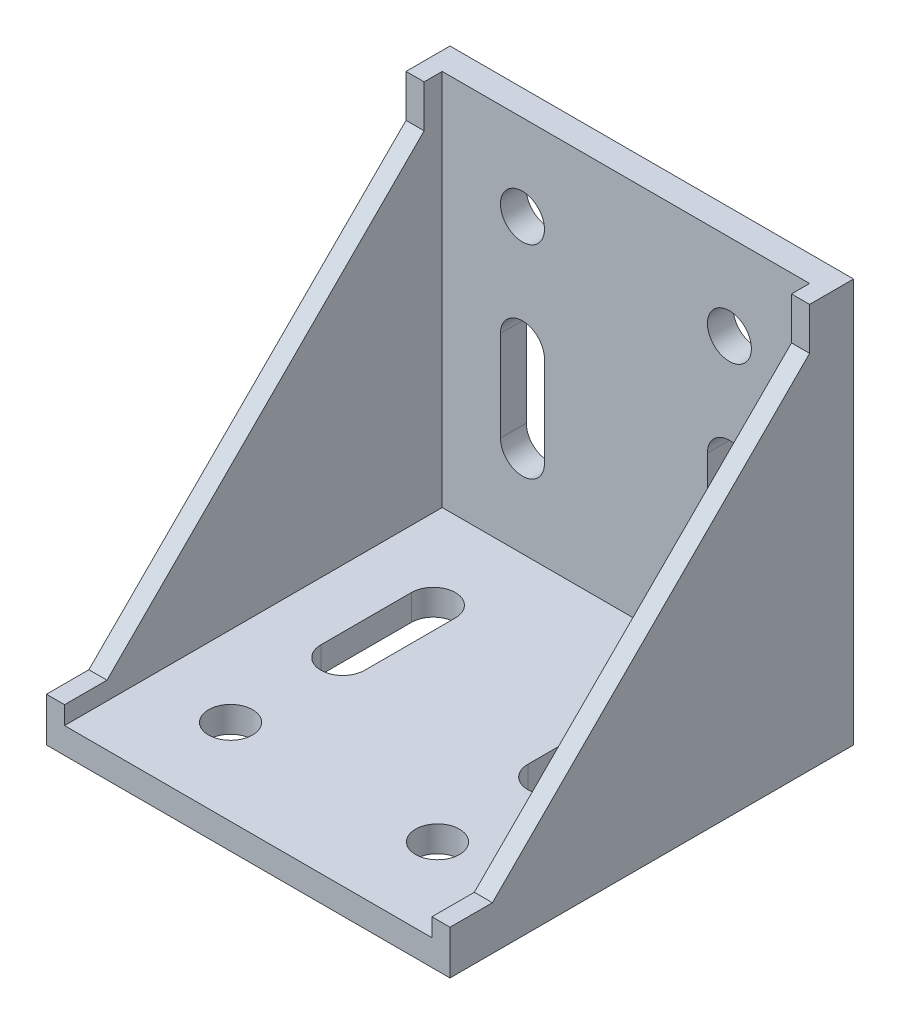
SolidWorks part; units mm, degrees
ref_plane "前视基准面" through (0, 0, 0) normal (0, 0, 1) x (1, 0, 0)
ref_plane "上视基准面" through (0, 0, 0) normal (0, 1, 0) x (1, 0, 0)
ref_plane "右视基准面" through (0, 0, 0) normal (1, 0, 0) x (0, 0, -1)
sketch "草图3" plane through (0, 0, 0) normal (0, 0, 1) x (1, 0, 0)
  line L1 (-39, 78) -> (39, 78)
  line L2 (-39, 78) -> (-39, 0)
  line L3 (-39, 0) -> (39, 0)
  line L4 (39, 78) -> (39, 0)
  line L7 (0, 111.3933) -> (0, -42.6526) construction
  line L11 (-39, 39) -> (39, 39) construction
  point P4 (0, 0)
  circle B0 centre (-20, 61.45) radius 4.25
  circle B1 centre (20, 61.45) radius 4.25
  line B2 (-15.75, 39.75) -> (-15.75, 22.25)
  arc B3 (-24.25, 22.25) -> (-15.75, 22.25) centre (-20, 22.25) ccw
  line B4 (-24.25, 39.75) -> (-24.25, 22.25)
  arc B5 (-15.75, 39.75) -> (-24.25, 39.75) centre (-20, 39.75) ccw
  line B6 (15.75, 39.75) -> (15.75, 22.25)
  arc B7 (24.25, 22.25) -> (15.75, 22.25) centre (20, 22.25) cw
  line B8 (24.25, 39.75) -> (24.25, 22.25)
  arc B9 (15.75, 39.75) -> (24.25, 39.75) centre (20, 39.75) cw
  dimension "D1" = 78
  dimension "D2" = 78
  dimension "D7" = 16.55
sketch_block_instance "块2-1"
sketch_block "块2"
sketch_block_instance "块1-1"
sketch_block "块1" parameters "D3"=8.5, "D1"=26, "D2"=8.5, "D4"=21.7
extrude "凸台-拉伸1" add sketch "草图3" along normal blind 5
sketch "草图4" plane through (-39, 0, 0) normal (-1, 0, 0) x (0, 0, 1)
  line L0 (5, 78) -> (8.5, 78)
  line L1 (8.5, 78) -> (8.5, 69.8)
  line L2 (8.5, 69.8) -> (69.8, 8.5)
  line L3 (69.8, 8.5) -> (78, 8.5)
  line L4 (78, 8.5) -> (78, 0)
  line L5 (78, 0) -> (5, 0)
  line L6 (5, 0) -> (5, 78)
  line L7 (0, 78) -> (0, 0) construction
  dimension "D1" = 8.5
  dimension "D2" = 8.5
  dimension "D3" = 78
  dimension "D4" = 8.2
extrude "凸台-拉伸2" add sketch "草图4" against normal blind 3.5
mirror "镜向1" about plane through (0, 0, 0) normal (1, 0, 0) of "凸台-拉伸2"
sketch "草图5" plane through (0, 0, 0) normal (0, -1, 0) x (1, 0, 0)
  line L0 (0, 98.3646) -> (0, -20.4361) construction
  line L1 (-39, 0) -> (39, 0)
  line L2 (-39, 0) -> (-39, 78)
  line L3 (-39, 78) -> (39, 78)
  line L4 (39, 0) -> (39, 78)
  line L5 (-39, 39) -> (39, 39) construction
  circle B0 centre (-20, 61.4142) radius 4.25
  circle B1 centre (20, 61.4142) radius 4.25
  line B2 (-15.75, 39.7142) -> (-15.75, 22.2142)
  arc B3 (-24.25, 22.2142) -> (-15.75, 22.2142) centre (-20, 22.2142) ccw
  line B4 (-24.25, 39.7142) -> (-24.25, 22.2142)
  arc B5 (-15.75, 39.7142) -> (-24.25, 39.7142) centre (-20, 39.7142) ccw
  line B6 (15.75, 39.7142) -> (15.75, 22.2142)
  arc B7 (24.25, 22.2142) -> (15.75, 22.2142) centre (20, 22.2142) cw
  line B8 (24.25, 39.7142) -> (24.25, 22.2142)
  arc B9 (15.75, 39.7142) -> (24.25, 39.7142) centre (20, 39.7142) cw
sketch_block_instance "块2-2"
extrude "凸台-拉伸3" add sketch "草图5" against normal blind 5
